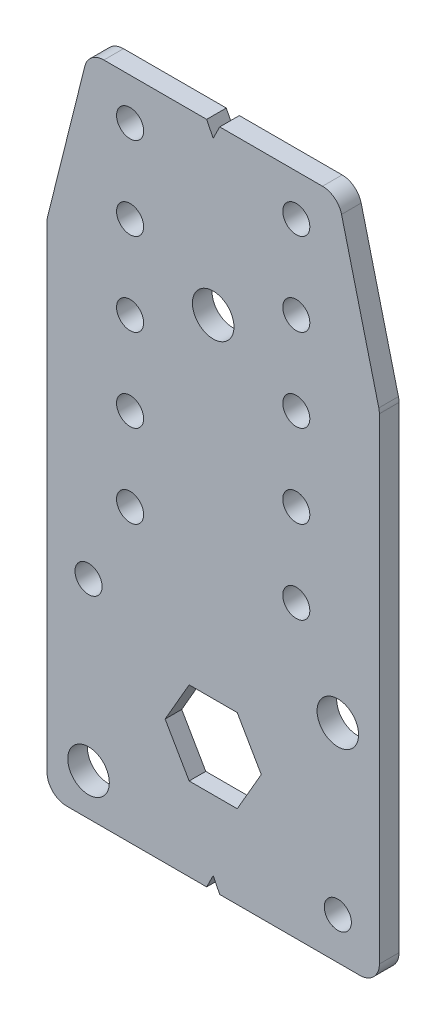
SolidWorks part; units mm, degrees
ref_plane "Front Plane" through (0, 0, 0) normal (0, 0, 1) x (1, 0, 0)
ref_plane "Top Plane" through (0, 0, 0) normal (0, 1, 0) x (1, 0, 0)
ref_plane "Right Plane" through (0, 0, 0) normal (1, 0, 0) x (0, 0, -1)
sketch "Sketch1" plane through (0, 0, 0) normal (0, 0, 1) x (1, 0, 0)
  line L0 (-19.05, 82.55) -> (19.05, 82.55)
  line L1 (-25.4, 57.15) -> (25.4, 57.15) construction
  line L2 (-25.4, 57.15) -> (-25.4, -19.05)
  line L3 (-25.4, -19.05) -> (25.4, -19.05)
  line L4 (25.4, 57.15) -> (25.4, -19.05)
  line L5 (-19.05, 82.55) -> (-25.4, 57.15)
  line L6 (19.05, 82.55) -> (25.4, 57.15)
  line L7 (-25.4, -12.7) -> (-19.05, -12.7) construction
  line L8 (-19.05, -12.7) -> (-19.05, -19.05) construction
  line L9 (19.05, 19.05) -> (19.05, 12.7) construction
  line L10 (-25.4, 19.05) -> (25.4, 19.05) construction
  line L11 (-25.4, 19.05) -> (-25.4, -19.05) construction
  line L12 (-25.4, -19.05) -> (25.4, -19.05) construction
  line L13 (25.4, 19.05) -> (25.4, -19.05) construction
  line L14 (-25.4, 19.05) -> (25.4, -19.05) construction
  line L15 (-25.4, -19.05) -> (25.4, 19.05) construction
  line L16 (19.05, 12.7) -> (25.4, 12.7) construction
  line L17 (-25.4, 12.7) -> (-19.05, 12.7) construction
  line L18 (-19.05, 12.7) -> (-19.05, 19.05) construction
  line L19 (19.05, -19.05) -> (19.05, -12.7) construction
  line L20 (19.05, -12.7) -> (25.4, -12.7) construction
  line L21 (0, 82.55) -> (0, 19.05) construction
  line L22 (12.7, 57.15) -> (12.7, 19.05) construction
  circle A0 centre (0, 0) radius 12.7
  circle A1 centre (-19.05, -12.7) radius 3.175
  circle A2 centre (19.05, 12.7) radius 3.175
  circle A3 centre (-19.05, 12.7) radius 2.07
  circle A4 centre (19.05, -12.7) radius 2.07
  circle A5 centre (0, 57.15) radius 3.175
  circle A6 centre (12.7, 25.4) radius 2.07
  circle A8 centre (12.7, 38.1) radius 2.07
  circle A9 centre (12.7, 50.8) radius 2.07
  circle A10 centre (12.7, 63.5) radius 2.07
  circle A11 centre (12.7, 76.2) radius 2.07
  circle A12 centre (-12.7, 25.4) radius 2.07
  circle A13 centre (-12.7, 38.1) radius 2.07
  circle A14 centre (-12.7, 50.8) radius 2.07
  circle A15 centre (-12.7, 63.5) radius 2.07
  circle A16 centre (-12.7, 76.2) radius 2.07
  point P8 (0, -19.05)
  point P10 (0, 82.55)
  dimension "D1" = 25.4
  dimension "D2" = 19.05
  dimension "D8" = 6.35
  dimension "D9" = 4.14
  dimension "D3" = 50.8
  dimension "D4" = 76.2
  dimension "D5" = 25.4
  dimension "D6" = 6.35
  dimension "D7" = 6.35
  dimension "D10" = 12.7
  dimension "D11" = 6.35
  dimension "D13" = 12.7
  dimension "D12" = 5
extrude "Boss-Extrude1" add sketch "Sketch1" along normal mid plane 3 contours L5 L2 L3 L4 L6 L0
fillet "Fillet1" radius 3 6 edges at (25.4, 57.15, 0) (25.4, -19.05, 0) (-25.4, -19.05, 0) (-25.4, 57.15, 0) (-19.05, 82.55, 0) (19.05, 82.55, 0)
sketch "Sketch2" plane through (0, 0, 1.5) normal (0, 0, 1) x (1, 0, 0)
  line L0 (0, 82.55) -> (0, -19.05) construction
  line L1 (16.7077, 82.55) -> (-16.7077, 82.55) construction
  line L2 (-22.4, -19.05) -> (22.4, -19.05) construction
  line L3 (-1, 82.55) -> (1, 82.55)
  line L4 (-1, 82.55) -> (0, 80.55)
  line L5 (1, 82.55) -> (0, 80.55)
  line L6 (0, 31.75) -> (-25.4, 31.75) construction
  line L7 (-25.4, 56.7807) -> (-25.4, -16.05) construction
  line L8 (-1, -19.05) -> (1, -19.05)
  line L9 (-1, -19.05) -> (0, -17.05)
  line L10 (1, -19.05) -> (0, -17.05)
  line L11 (-5.08, 17.78) -> (5.08, 17.78)
  line L12 (5.08, 17.78) -> (5.08, 11.6397)
  line L13 (-5.08, 17.78) -> (-5.08, 11.6397)
  circle A0 centre (0, 0) radius 12.7 construction
  arc A1 (0, -12.7) -> (-5.08, 11.6397) centre (0, 0) ccw
  arc A2 (-5.08, 11.6397) -> (0, -12.7) centre (0, 0) ccw construction
  point P8 (0, 82.55)
  point P20 (0, 17.78)
  circle M15 centre (0, 0) radius 12.7
  line M20 (16.7077, 82.55) -> (-16.7077, 82.55)
  line M26 (-22.4, -19.05) -> (22.4, -19.05)
  dimension "D1" = 2
  dimension "D2" = 2
  dimension "D3" = 10.16
  dimension "D4" = 17.78
extrude "Cut-Extrude1" cut sketch "Sketch2" against normal blind 3 contours L11 L13 L12 M15 | L10 L9 M26 | L5 L4 M20
sketch "Sketch3" plane through (0, 0, 1.5) normal (0, 0, 1) x (1, 0, 0)
  line L0 (5.08, 17.78) -> (5.08, 11.6397) construction
  line L1 (-5.08, 17.78) -> (-5.08, 11.6397) construction
  line L2 (-5.08, 17.78) -> (5.08, 17.78) construction
  line L3 (5.08, 17.78) -> (5.08, 11.6397)
  line L4 (-5.08, 17.78) -> (-5.08, 11.6397)
  line L5 (-5.08, 17.78) -> (5.08, 17.78)
  line L7 (7.347, 0) -> (3.6735, 6.3627)
  line L8 (3.6735, 6.3627) -> (-3.6735, 6.3627)
  line L9 (-3.6735, 6.3627) -> (-7.347, 0)
  line L10 (-7.347, 0) -> (-3.6735, -6.3627)
  line L11 (-3.6735, -6.3627) -> (3.6735, -6.3627)
  line L12 (3.6735, -6.3627) -> (7.347, 0)
  arc A0 (-5.08, 11.6397) -> (5.08, 11.6397) centre (0, 0) ccw construction
  arc A2 (-5.08, 11.6397) -> (5.08, 11.6397) centre (0, 0) ccw
  circle A3 centre (0, 0) radius 6.3627 construction
  dimension "D1" = 12.7254
extrude "Boss-Extrude3" add sketch "Sketch3" against normal blind 2.54
